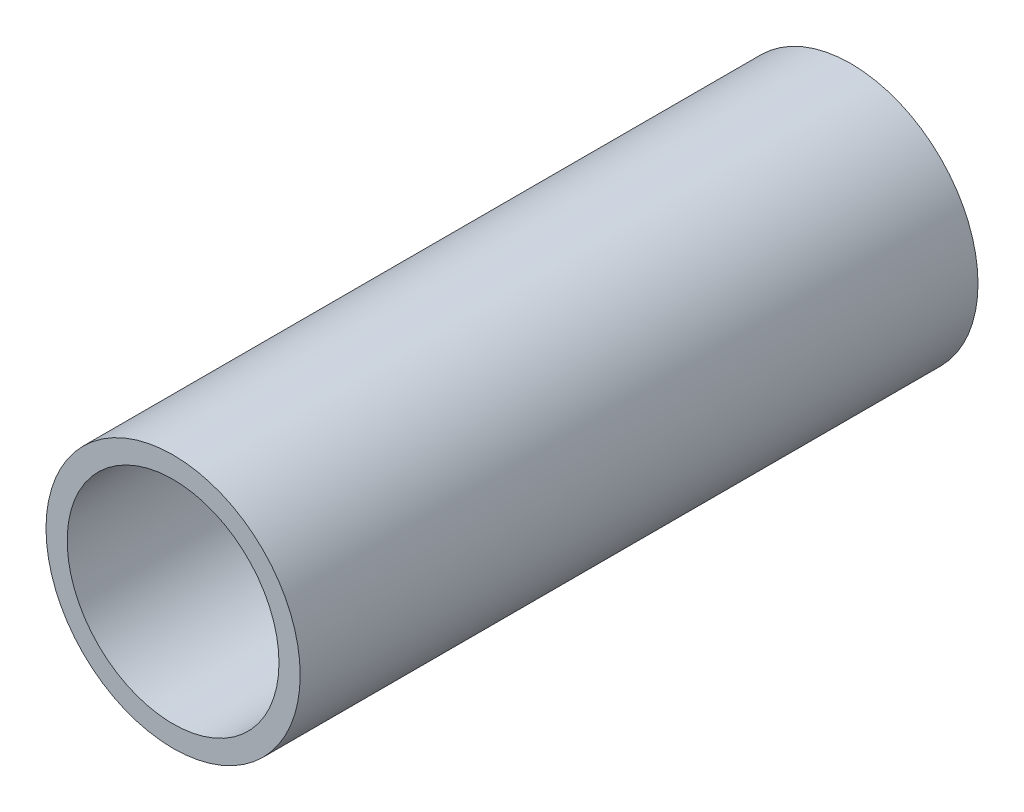
SolidWorks part; units mm, degrees
ref_plane "Front Plane" through (0, 0, 0) normal (0, 0, 1) x (1, 0, 0)
ref_plane "Top Plane" through (0, 0, 0) normal (0, 1, 0) x (1, 0, 0)
ref_plane "Right Plane" through (0, 0, 0) normal (1, 0, 0) x (0, 0, -1)
sketch "Sketch1" plane through (0, 0, 0) normal (0, 0, 1) x (1, 0, 0)
  circle A0 centre (0, 0) radius 30
  circle A1 centre (0, 0) radius 25
  dimension "D1" = 60
  dimension "D2" = 5
extrude "Boss-Extrude1" add sketch "Sketch1" along normal blind 160
